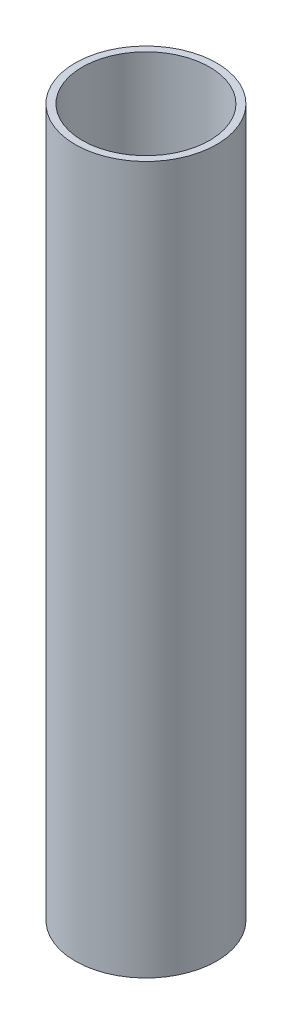
SolidWorks part; units mm, degrees
material "Thornel Mat VMA"
ref_plane "Front Plane" through (0, 0, 0) normal (0, 0, 1) x (1, 0, 0)
ref_plane "Top Plane" through (0, 0, 0) normal (0, 1, 0) x (1, 0, 0)
ref_plane "Right Plane" through (0, 0, 0) normal (1, 0, 0) x (0, 0, -1)
sketch "Sketch1" plane through (0, 0, 0) normal (0, 1, 0) x (1, 0, 0)
  circle A0 centre (0, 0) radius 18
  circle A1 centre (0, 0) radius 20
  dimension "D1" = 40
  dimension "D2" = 2
extrude "Boss-Extrude1" add sketch "Sketch1" along normal blind 200
